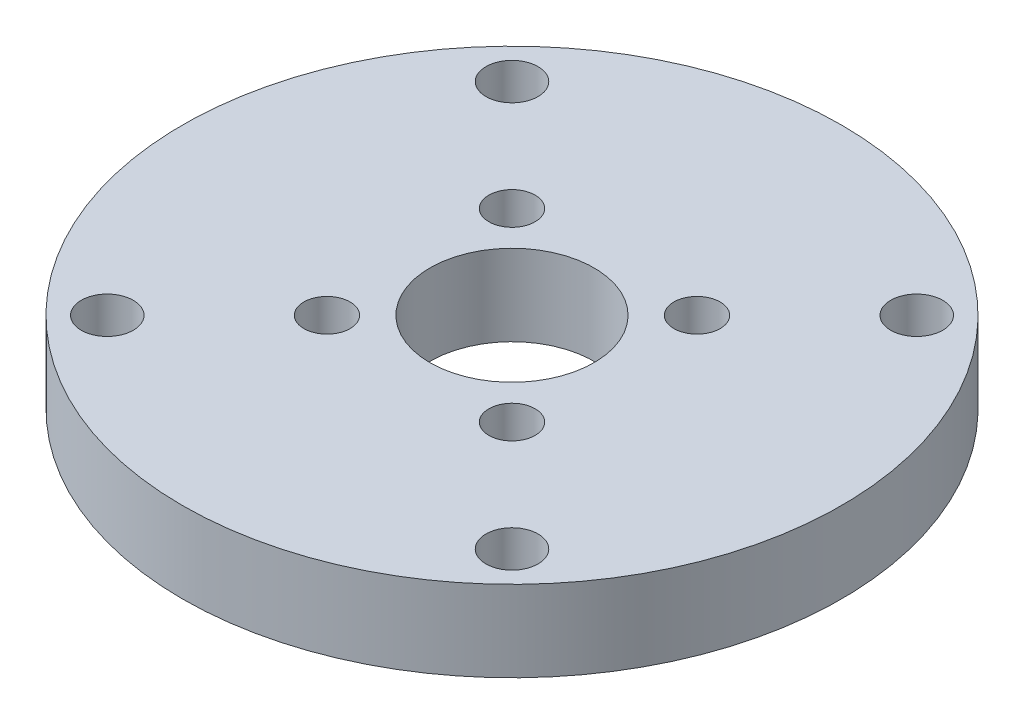
SolidWorks part; units mm, degrees
ref_plane "Front Plane" through (0, 0, 0) normal (0, 0, 1) x (1, 0, 0)
ref_plane "Top Plane" through (0, 0, 0) normal (0, 1, 0) x (1, 0, 0)
ref_plane "Right Plane" through (0, 0, 0) normal (1, 0, 0) x (0, 0, -1)
sketch "Sketch1" plane through (0, 0, 0) normal (0, 1, 0) x (1, 0, 0)
  circle A0 centre (0, 0) radius 28.5
  dimension "D1" = 57
extrude "Boss-Extrude1" add sketch "Sketch1" along normal mid plane 7
sketch "Sketch2" plane through (0, 3.5, 0) normal (0, 1, 0) x (1, 0, 0)
  line L0 (0, 0) -> (20.1525, 20.1525) construction
  line L1 (0, 0) -> (28.5, 0) construction
  line L2 (14.8492, 14.8492) -> (20.1525, 20.1525) construction
  line L4 (8, 8) -> (-8, 8) construction
  line L5 (8, 8) -> (8, -8) construction
  line L6 (8, -8) -> (-8, -8) construction
  line L7 (-8, 8) -> (-8, -8) construction
  line L8 (0, -8) -> (0, 8) construction
  line L9 (8, 0) -> (-8, 0) construction
  circle A0 centre (0, 0) radius 28.5 construction
  circle A1 centre (0, 0) radius 21 construction
  circle A2 centre (17.5009, 17.5009) radius 2.25
  circle A3 centre (17.5009, -17.5009) radius 2.25
  circle A4 centre (-17.5009, -17.5009) radius 2.25
  circle A5 centre (-17.5009, 17.5009) radius 2.25
  circle A6 centre (-8, -8) radius 2
  circle A7 centre (-8, 8) radius 2
  circle A8 centre (8, 8) radius 2
  circle A9 centre (8, -8) radius 2
  point P19 (0, 0)
  dimension "D2" = 42
  dimension "D3" = 4.5
  dimension "D5" = 4
  dimension "D1" = 45
  dimension "D6" = 16
  dimension "D4" = 4
extrude "Cut-Extrude1" cut sketch "Sketch2" against normal through all
sketch "Sketch3" plane through (0, 3.5, 0) normal (0, 1, 0) x (1, 0, 0)
  circle A0 centre (0, 0) radius 7.1
  dimension "D1" = 14.2
extrude "Cut-Extrude2" cut sketch "Sketch3" against normal through all
